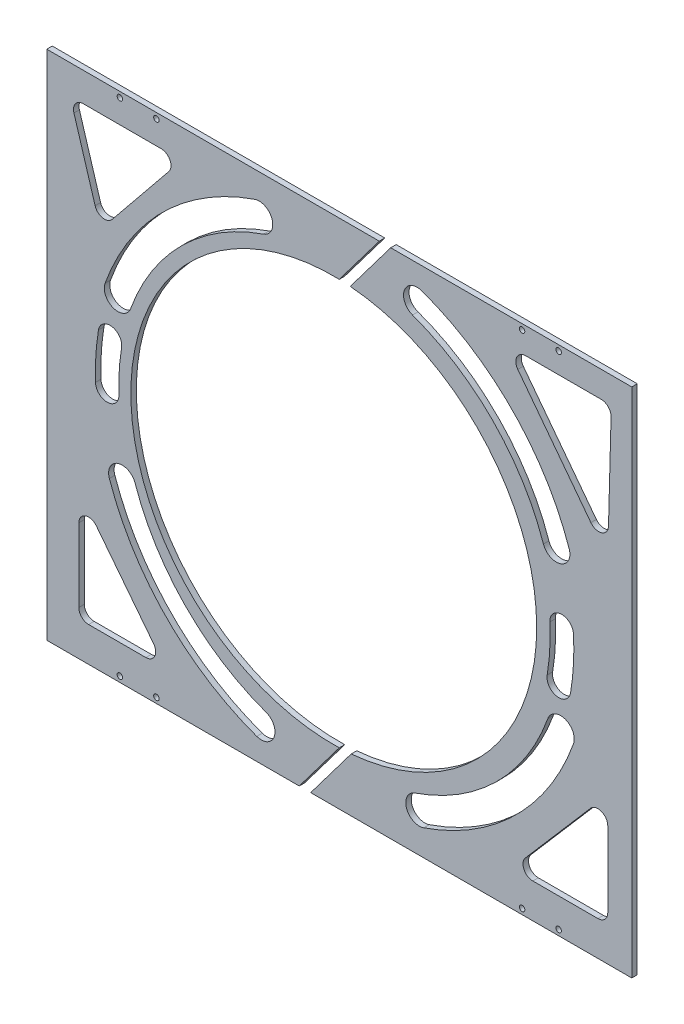
SolidWorks part; units mm, degrees
material "Thornel Mat VMA"
ref_plane "前视基准面" through (0, 0, 0) normal (0, 0, 1) x (1, 0, 0)
ref_plane "上视基准面" through (0, 0, 0) normal (0, 1, 0) x (1, 0, 0)
ref_plane "右视基准面" through (0, 0, 0) normal (1, 0, 0) x (0, 0, -1)
sketch "草图1" plane through (0, 0, 0) normal (0, 0, 1) x (1, 0, 0)
  line L0 (21.8836, 140) -> (0, 110.9595)
  line L1 (-160, 140) -> (160, 140)
  line L2 (-160, 140) -> (-160, -140)
  line L3 (-160, -140) -> (160, -140)
  line L4 (160, 140) -> (160, -140)
  line L5 (-160, 140) -> (160, -140) construction
  line L6 (-160, -140) -> (160, 140) construction
  line L7 (0, -110.9595) -> (-21.8836, -140)
  line L8 (28.1443, 140) -> (6.0149, 110.6333)
  line L9 (-15.6229, -140) -> (6.5396, -110.5893)
  line L10 (0, 110.9595) -> (0, -110.9595) construction
  line L11 (0, 0) -> (-3, 0) construction
  circle A4 centre (-3, 0) radius 111
  point P0 (0, 0)
  dimension "D3" = 3
  dimension "D7" = 222
  dimension "D1" = 280
  dimension "D2" = 320
  dimension "D4" = 5
  dimension "D5" = 5
  dimension "D6" = 53
extrude "凸台-拉伸1" add sketch "草图1" along normal mid plane 3
sketch "草图2" plane through (0, 0, -1.5) normal (0, 0, -1) x (-1, 0, 0)
  circle A0 centre (-120, -137) radius 1.5 construction
  circle A1 centre (-100, -137) radius 1.5 construction
  circle A2 centre (100, -137) radius 1.5 construction
  circle A3 centre (120, -137) radius 1.5 construction
  circle A4 centre (-120, 137) radius 1.5 construction
  circle A5 centre (-100, 137) radius 1.5 construction
  circle A6 centre (100, 137) radius 1.5 construction
  circle A7 centre (120, 137) radius 1.5 construction
  circle A8 centre (-120, -137) radius 1.5
  circle A9 centre (-100, -137) radius 1.5
  circle A10 centre (100, -137) radius 1.5
  circle A11 centre (120, -137) radius 1.5
  circle A12 centre (-120, 137) radius 1.5
  circle A13 centre (-100, 137) radius 1.5
  circle A14 centre (100, 137) radius 1.5
  circle A15 centre (120, 137) radius 1.5
extrude "切除-拉伸1" cut sketch "草图2" against normal blind 3
sketch "草图4" plane through (0, 0, 1.5) normal (0, 0, 1) x (1, 0, 0)
  line L0 (0, 0) -> (-3, 0) construction
  line L1 (-3, 0) -> (-3, -100.2692) construction
  line L2 (-139.9924, 124.1474) -> (-97.418, 124.1474)
  line L3 (-93.2486, 115.3927) -> (-124.2307, 77.2257)
  line L4 (-133.5385, 79.0496) -> (-145.1308, 117.2166)
  line L5 (-142.4557, -75.5885) -> (-142.4557, -115.7218)
  line L6 (-137.0855, -121.092) -> (-105.7841, -121.092)
  line L7 (-101.5496, -112.4191) -> (-132.8509, -72.2859)
  line L8 (101.9334, 125.7485) -> (143.3066, 125.7485)
  line L9 (148.6749, 120.2355) -> (147.2764, 67.6614)
  line L10 (137.6333, 64.5539) -> (97.6586, 117.128)
  line L11 (146.8706, -74.4182) -> (146.8706, -115.7218)
  line L12 (141.5004, -121.092) -> (105.8713, -121.092)
  line L13 (101.8049, -112.2141) -> (137.4341, -70.9105)
  arc A0 (-43.826, 118.715) -> (-121.092, 42.5947) centre (-3, 0) ccw construction
  arc A1 (-46.2448, 125.7485) -> (-128.0886, 45.1183) centre (-3, 0) ccw
  arc A2 (-41.4071, 111.6815) -> (-114.0954, 40.071) centre (-3, 0) ccw
  arc A3 (-41.4071, 111.6815) -> (-46.2448, 125.7485) centre (-43.826, 118.715) ccw
  arc A4 (-128.0886, 45.1183) -> (-114.0954, 40.071) centre (-121.092, 42.5947) ccw
  arc A5 (111.6815, 41.4071) -> (40.071, 114.0954) centre (0, 3) ccw
  arc A6 (111.6815, 41.4071) -> (125.7485, 46.2448) centre (118.715, 43.826) ccw
  arc A7 (45.1183, 128.0886) -> (40.071, 114.0954) centre (42.5947, 121.092) ccw
  arc A8 (125.7485, 46.2448) -> (45.1183, 128.0886) centre (0, 3) ccw
  arc A9 (118.715, 43.826) -> (42.5947, 121.092) centre (0, 3) ccw construction
  arc A10 (41.4071, -111.6815) -> (114.0954, -40.071) centre (3, 0) ccw
  arc A11 (41.4071, -111.6815) -> (46.2448, -125.7485) centre (43.826, -118.715) ccw
  arc A12 (128.0886, -45.1183) -> (114.0954, -40.071) centre (121.092, -42.5947) ccw
  arc A13 (46.2448, -125.7485) -> (128.0886, -45.1183) centre (3, 0) ccw
  arc A14 (43.826, -118.715) -> (121.092, -42.5947) centre (3, 0) ccw construction
  arc A15 (-111.6815, -41.4071) -> (-40.071, -114.0954) centre (0, -3) ccw
  arc A16 (-111.6815, -41.4071) -> (-125.7485, -46.2448) centre (-118.715, -43.826) ccw
  arc A17 (-45.1183, -128.0886) -> (-40.071, -114.0954) centre (-42.5947, -121.092) ccw
  arc A18 (-125.7485, -46.2448) -> (-45.1183, -128.0886) centre (0, -3) ccw
  arc A19 (-118.715, -43.826) -> (-42.5947, -121.092) centre (0, -3) ccw construction
  arc A20 (-125.392, 20.0752) -> (-126.9529, -4.3006) centre (-3, 0) ccw construction
  arc A21 (-131.7194, 21.1131) -> (-133.361, -4.523) centre (-3, 0) ccw
  arc A22 (-119.0646, 19.0374) -> (-120.5448, -4.0783) centre (-3, 0) ccw
  arc A23 (-119.0646, 19.0374) -> (-131.7194, 21.1131) centre (-125.392, 20.0752) ccw
  arc A24 (-133.361, -4.523) -> (-120.5448, -4.0783) centre (-126.9529, -4.3006) ccw
  arc A25 (121.6669, 6.6183) -> (120.1195, -20.6691) centre (-3, 0) cw construction
  arc A26 (126.5041, -21.7409) -> (128.1317, 6.9615) centre (-3, 0) ccw
  arc A27 (113.7349, -19.5972) -> (115.202, 6.275) centre (-3, 0) ccw
  arc A28 (113.7349, -19.5972) -> (126.5041, -21.7409) centre (120.1195, -20.6691) ccw
  arc A29 (128.1317, 6.9615) -> (115.202, 6.275) centre (121.6669, 6.6183) ccw
  arc A30 (-105.7841, -121.092) -> (-101.5496, -112.4191) centre (-105.7841, -115.7218) ccw
  arc A31 (-132.8509, -72.2859) -> (-142.4557, -75.5885) centre (-137.0855, -75.5885) ccw
  arc A32 (-137.0855, -121.092) -> (-142.4557, -115.7218) centre (-137.0855, -115.7218) cw
  arc A33 (141.5004, -121.092) -> (146.8706, -115.7218) centre (141.5004, -115.7218) ccw
  arc A34 (105.8713, -121.092) -> (101.8049, -112.2141) centre (105.8713, -115.7218) cw
  arc A35 (146.8706, -74.4182) -> (137.4341, -70.9105) centre (141.5004, -74.4182) ccw
  arc A36 (147.2764, 67.6614) -> (137.6333, 64.5539) centre (141.9081, 67.8042) cw
  arc A37 (143.3066, 125.7485) -> (148.6749, 120.2355) centre (143.3066, 120.3783) cw
  arc A38 (97.6586, 117.128) -> (101.9334, 125.7485) centre (101.9334, 120.3783) cw
  arc A39 (-93.2486, 115.3927) -> (-97.418, 124.1474) centre (-97.418, 118.7772) ccw
  arc A40 (-145.1308, 117.2166) -> (-139.9924, 124.1474) centre (-139.9924, 118.7772) cw
  arc A41 (-124.2307, 77.2257) -> (-133.5385, 79.0496) centre (-128.4001, 80.6103) cw
  point P5 (-91.1039, 89.4299)
  point P16 (89.4299, 91.1039)
  point P24 (91.1039, -89.4299)
  point P32 (-89.4299, -91.1039)
  point P37 (0, 0)
  point P38 (-126.774, 7.9258)
  point P47 (121.6422, -7.0679)
  point P79 (146.8706, 52.4051)
  dimension "D2" = 4
  dimension "D3" = 5.3702
  dimension "D1" = 3
extrude "切除-拉伸3" cut sketch "草图4" against normal blind 3
